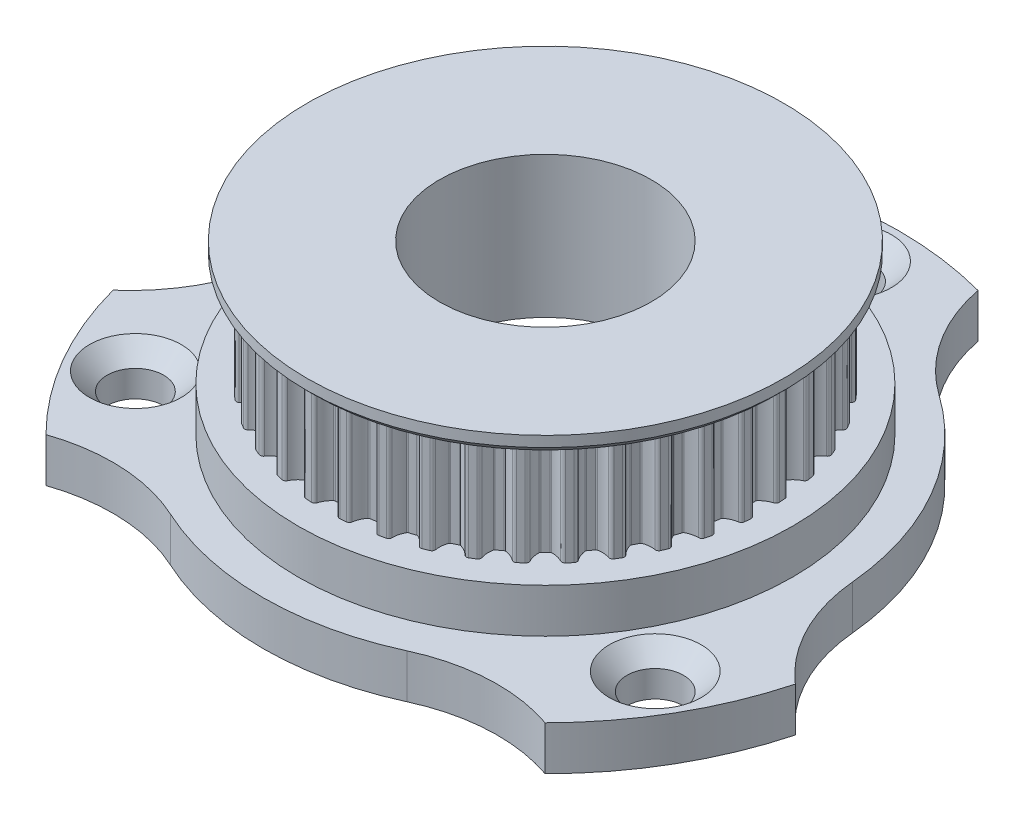
SolidWorks part; units mm, degrees
ref_plane "Front Plane" through (0, 0, 0) normal (0, 0, 1) x (1, 0, 0)
ref_plane "Top Plane" through (0, 0, 0) normal (0, 1, 0) x (1, 0, 0)
ref_plane "Right Plane" through (0, 0, 0) normal (1, 0, 0) x (0, 0, -1)
sketch "Sketch1" plane through (0, 0, 0) normal (0, 1, 0) x (1, 0, 0)
  line L0 (0, 0) -> (0, 17) construction
  circle A1 centre (0, 0) radius 13
  circle A2 centre (0, 17) radius 1.6
  circle A3 centre (14.7224, -8.5) radius 1.6
  circle A4 centre (-14.7224, -8.5) radius 1.6
  arc A7 (-9.2308, 13.0688) -> (-5.1862, 19.3159) centre (-15, 21.2368) ccw
  arc A8 (-9.2308, 13.0688) -> (-15.9333, 1.4597) centre (0, 0) ccw
  arc A9 (-19.3212, -5.1665) -> (-15.9333, 1.4597) centre (-25.8916, 2.372) ccw
  arc A10 (-6.7025, -14.5285) -> (-14.1349, -14.1493) centre (-10.8916, -23.6088) ccw
  arc A11 (-6.7025, -14.5285) -> (6.7025, -14.5285) centre (0, 0) ccw
  arc A12 (14.1349, -14.1493) -> (6.7025, -14.5285) centre (10.8916, -23.6088) ccw
  arc A13 (15.9333, 1.4597) -> (19.3212, -5.1665) centre (25.8916, 2.372) ccw
  arc A14 (15.9333, 1.4597) -> (9.2308, 13.0688) centre (0, 0) ccw
  arc A15 (5.1862, 19.3159) -> (9.2308, 13.0688) centre (15, 21.2368) ccw
  arc A16 (-19.3212, -5.1665) -> (-14.1349, -14.1493) centre (0, 0) ccw
  arc A17 (5.1862, 19.3159) -> (-5.1862, 19.3159) centre (0, 0) ccw
  arc A18 (14.1349, -14.1493) -> (19.3212, -5.1665) centre (0, 0) ccw
  point P13 (0, 0)
  dimension "D1" = 40
  dimension "D2" = 26
  dimension "D3" = 3.2
  dimension "D4" = 17
  dimension "D5" = 3
extrude "Boss-Extrude1" add sketch "Sketch1" along normal blind 4
sketch "Sketch2" plane through (0, 4, 0) normal (0, 1, 0) x (1, 0, 0)
  circle A0 centre (0, 0) radius 14
  dimension "D1" = 28
extrude "Boss-Extrude2" add sketch "Sketch2" along normal blind 1
sketch "Sketch3" plane through (0, 5, 0) normal (0, 1, 0) x (1, 0, 0)
  circle B0 centre (0, 0) radius 1
  arc B1 (0.8079, 12.4518) -> (0.6143, 12.319) centre (0.7956, 12.2622) ccw
  arc B2 (0.2503, 11.7432) -> (0.6143, 12.319) centre (-0.65, 12.7154) ccw
  arc B3 (0.1808, 11.7166) -> (0.2503, 11.7432) centre (0.1823, 11.8166) ccw
  arc B4 (0.1808, 11.7166) -> (-0.1808, 11.7166) centre (0, 0) ccw
  arc B5 (-0.2503, 11.7432) -> (-0.1808, 11.7166) centre (-0.1823, 11.8166) ccw
  arc B6 (-0.6143, 12.319) -> (-0.2503, 11.7432) centre (0.65, 12.7154) ccw
  arc B7 (-0.6143, 12.319) -> (-0.8079, 12.4518) centre (-0.7956, 12.2622) ccw
  arc B8 (-0.8079, 12.4518) -> (-1.1499, 12.4249) centre (0, 0) ccw
  arc B9 (-1.1499, 12.4249) -> (-1.3204, 12.2635) centre (-1.1324, 12.2357) ccw
  arc B10 (-1.5898, 11.6378) -> (-1.3204, 12.2635) centre (-2.6311, 12.4572) ccw
  arc B11 (-1.6543, 11.6006) -> (-1.5898, 11.6378) centre (-1.6684, 11.6996) ccw
  arc B12 (-1.6543, 11.6006) -> (-2.0114, 11.5441) centre (0, 0) ccw
  arc B13 (-2.0842, 11.5595) -> (-2.0114, 11.5441) centre (-2.0286, 11.6426) ccw
  arc B14 (-2.5339, 12.0713) -> (-2.0842, 11.5595) centre (-1.3471, 12.6605) ccw
  arc B15 (-2.5339, 12.0713) -> (-2.7459, 12.1721) centre (-2.7041, 11.9868) ccw
  arc B16 (-2.7459, 12.1721) -> (-3.0794, 12.092) centre (0, 0) ccw
  arc B17 (-3.0794, 12.092) -> (-3.2225, 11.906) centre (-3.0325, 11.9079) ccw
  arc B18 (-3.3908, 11.2458) -> (-3.2225, 11.906) centre (-4.5475, 11.8922) ccw
  arc B19 (-3.4487, 11.199) -> (-3.3908, 11.2458) centre (-3.4781, 11.2946) ccw
  arc B20 (-3.4487, 11.199) -> (-3.7926, 11.0873) centre (0, 0) ccw
  arc B21 (-3.8669, 11.0911) -> (-3.7926, 11.0873) centre (-3.8249, 11.1819) ccw
  arc B22 (-4.3911, 11.5263) -> (-3.8669, 11.0911) centre (-3.3111, 12.2939) ccw
  arc B23 (-4.3911, 11.5263) -> (-4.6162, 11.5927) centre (-4.5459, 11.4162) ccw
  arc B24 (-4.6162, 11.5927) -> (-4.9331, 11.4614) centre (0, 0) ccw
  arc B25 (-4.9331, 11.4614) -> (-5.0454, 11.2553) centre (-4.858, 11.2869) ccw
  arc B26 (-5.1083, 10.5769) -> (-5.0454, 11.2553) centre (-6.3518, 11.0344) ccw
  arc B27 (-5.1581, 10.5216) -> (-5.1083, 10.5769) centre (-5.2022, 10.6114) ccw
  arc B28 (-5.1581, 10.5216) -> (-5.4803, 10.3575) centre (0, 0) ccw
  arc B29 (-5.5543, 10.3497) -> (-5.4803, 10.3575) centre (-5.5271, 10.4459) ccw
  arc B30 (-6.1401, 10.6975) -> (-5.5543, 10.3497) centre (-5.1935, 11.6246) ccw
  arc B31 (-6.1401, 10.6975) -> (-6.3729, 10.7279) centre (-6.2758, 10.5645) ccw
  arc B32 (-6.3729, 10.7279) -> (-6.6654, 10.5486) centre (0, 0) ccw
  arc B33 (-6.6654, 10.5486) -> (-6.744, 10.3274) centre (-6.5639, 10.388) ccw
  arc B34 (-6.7, 9.6476) -> (-6.744, 10.3274) centre (-7.9998, 9.9049) ccw
  arc B35 (-6.7406, 9.5852) -> (-6.7, 9.6476) centre (-6.7981, 9.667) ccw
  arc B36 (-6.7406, 9.5852) -> (-7.0331, 9.3727) centre (0, 0) ccw
  arc B37 (-7.105, 9.3534) -> (-7.0331, 9.3727) centre (-7.0931, 9.4527) ccw
  arc B38 (-7.738, 9.6052) -> (-7.105, 9.3534) centre (-6.9481, 10.669) ccw
  arc B39 (-7.738, 9.6052) -> (-7.9726, 9.5988) centre (-7.8512, 9.4527) ccw
  arc B40 (-7.9726, 9.5988) -> (-8.2335, 9.3761) centre (0, 0) ccw
  arc B41 (-8.2335, 9.3761) -> (-8.2765, 9.1453) centre (-8.1081, 9.2333) ccw
  arc B42 (-8.1267, 8.4807) -> (-8.2765, 9.1453) centre (-9.4508, 8.5315) ccw
  arc B43 (-8.1571, 8.4127) -> (-8.1267, 8.4807) centre (-8.2267, 8.4845) ccw
  arc B44 (-8.1571, 8.4127) -> (-8.4127, 8.1571) centre (0, 0) ccw
  arc B45 (-8.4807, 8.1267) -> (-8.4127, 8.1571) centre (-8.4845, 8.2267) ccw
  arc B46 (-9.1453, 8.2765) -> (-8.4807, 8.1267) centre (-8.5315, 9.4508) ccw
  arc B47 (-9.1453, 8.2765) -> (-9.3761, 8.2335) centre (-9.2333, 8.1081) ccw
  arc B48 (-9.3761, 8.2335) -> (-9.5988, 7.9726) centre (0, 0) ccw
  arc B49 (-9.5988, 7.9726) -> (-9.6052, 7.738) centre (-9.4527, 7.8512) ccw
  arc B50 (-9.3534, 7.105) -> (-9.6052, 7.738) centre (-10.669, 6.9481) ccw
  arc B51 (-9.3727, 7.0331) -> (-9.3534, 7.105) centre (-9.4527, 7.0931) ccw
  arc B52 (-9.3727, 7.0331) -> (-9.5852, 6.7406) centre (0, 0) ccw
  arc B53 (-9.6476, 6.7) -> (-9.5852, 6.7406) centre (-9.667, 6.7981) ccw
  arc B54 (-10.3274, 6.744) -> (-9.6476, 6.7) centre (-9.9049, 7.9998) ccw
  arc B55 (-10.3274, 6.744) -> (-10.5486, 6.6654) centre (-10.388, 6.5639) ccw
  arc B56 (-10.5486, 6.6654) -> (-10.7279, 6.3729) centre (0, 0) ccw
  arc B57 (-10.7279, 6.3729) -> (-10.6975, 6.1401) centre (-10.5645, 6.2758) ccw
  arc B58 (-10.3497, 5.5543) -> (-10.6975, 6.1401) centre (-11.6246, 5.1935) ccw
  arc B59 (-10.3575, 5.4803) -> (-10.3497, 5.5543) centre (-10.4459, 5.5271) ccw
  arc B60 (-10.3575, 5.4803) -> (-10.5216, 5.1581) centre (0, 0) ccw
  arc B61 (-10.5769, 5.1083) -> (-10.5216, 5.1581) centre (-10.6114, 5.2022) ccw
  arc B62 (-11.2553, 5.0454) -> (-10.5769, 5.1083) centre (-11.0344, 6.3518) ccw
  arc B63 (-11.2553, 5.0454) -> (-11.4614, 4.9331) centre (-11.2869, 4.858) ccw
  arc B64 (-11.4614, 4.9331) -> (-11.5927, 4.6162) centre (0, 0) ccw
  arc B65 (-11.5927, 4.6162) -> (-11.5263, 4.3911) centre (-11.4162, 4.5459) ccw
  arc B66 (-11.0911, 3.8669) -> (-11.5263, 4.3911) centre (-12.2939, 3.3111) ccw
  arc B67 (-11.0873, 3.7926) -> (-11.0911, 3.8669) centre (-11.1819, 3.8249) ccw
  arc B68 (-11.0873, 3.7926) -> (-11.199, 3.4487) centre (0, 0) ccw
  arc B69 (-11.2458, 3.3908) -> (-11.199, 3.4487) centre (-11.2946, 3.4781) ccw
  arc B70 (-11.906, 3.2225) -> (-11.2458, 3.3908) centre (-11.8922, 4.5475) ccw
  arc B71 (-11.906, 3.2225) -> (-12.092, 3.0794) centre (-11.9079, 3.0325) ccw
  arc B72 (-12.092, 3.0794) -> (-12.1721, 2.7459) centre (0, 0) ccw
  arc B73 (-12.1721, 2.7459) -> (-12.0713, 2.5339) centre (-11.9868, 2.7041) ccw
  arc B74 (-11.5595, 2.0842) -> (-12.0713, 2.5339) centre (-12.6605, 1.3471) ccw
  arc B75 (-11.5441, 2.0114) -> (-11.5595, 2.0842) centre (-11.6426, 2.0286) ccw
  arc B76 (-11.5441, 2.0114) -> (-11.6006, 1.6543) centre (0, 0) ccw
  arc B77 (-11.6378, 1.5898) -> (-11.6006, 1.6543) centre (-11.6996, 1.6684) ccw
  arc B78 (-12.2635, 1.3204) -> (-11.6378, 1.5898) centre (-12.4572, 2.6311) ccw
  arc B79 (-12.2635, 1.3204) -> (-12.4249, 1.1499) centre (-12.2357, 1.1324) ccw
  arc B80 (-12.4249, 1.1499) -> (-12.4518, 0.8079) centre (0, 0) ccw
  arc B81 (-12.4518, 0.8079) -> (-12.319, 0.6143) centre (-12.2622, 0.7956) ccw
  arc B82 (-11.7432, 0.2503) -> (-12.319, 0.6143) centre (-12.7154, -0.65) ccw
  arc B83 (-11.7166, 0.1808) -> (-11.7432, 0.2503) centre (-11.8166, 0.1823) ccw
  arc B84 (-11.7166, 0.1808) -> (-11.7166, -0.1808) centre (0, 0) ccw
  arc B85 (-11.7432, -0.2503) -> (-11.7166, -0.1808) centre (-11.8166, -0.1823) ccw
  arc B86 (-12.319, -0.6143) -> (-11.7432, -0.2503) centre (-12.7154, 0.65) ccw
  arc B87 (-12.319, -0.6143) -> (-12.4518, -0.8079) centre (-12.2622, -0.7956) ccw
  arc B88 (-12.4518, -0.8079) -> (-12.4249, -1.1499) centre (0, 0) ccw
  arc B89 (-12.4249, -1.1499) -> (-12.2635, -1.3204) centre (-12.2357, -1.1324) ccw
  arc B90 (-11.6378, -1.5898) -> (-12.2635, -1.3204) centre (-12.4572, -2.6311) ccw
  arc B91 (-11.6006, -1.6543) -> (-11.6378, -1.5898) centre (-11.6996, -1.6684) ccw
  arc B92 (-11.6006, -1.6543) -> (-11.5441, -2.0114) centre (0, 0) ccw
  arc B93 (-11.5595, -2.0842) -> (-11.5441, -2.0114) centre (-11.6426, -2.0286) ccw
  arc B94 (-12.0713, -2.5339) -> (-11.5595, -2.0842) centre (-12.6605, -1.3471) ccw
  arc B95 (-12.0713, -2.5339) -> (-12.1721, -2.7459) centre (-11.9868, -2.7041) ccw
  arc B96 (-12.1721, -2.7459) -> (-12.092, -3.0794) centre (0, 0) ccw
  arc B97 (-12.092, -3.0794) -> (-11.906, -3.2225) centre (-11.9079, -3.0325) ccw
  arc B98 (-11.2458, -3.3908) -> (-11.906, -3.2225) centre (-11.8922, -4.5475) ccw
  arc B99 (-11.199, -3.4487) -> (-11.2458, -3.3908) centre (-11.2946, -3.4781) ccw
  arc B100 (-11.199, -3.4487) -> (-11.0873, -3.7926) centre (0, 0) ccw
  arc B101 (-11.0911, -3.8669) -> (-11.0873, -3.7926) centre (-11.1819, -3.8249) ccw
  arc B102 (-11.5263, -4.3911) -> (-11.0911, -3.8669) centre (-12.2939, -3.3111) ccw
  arc B103 (-11.5263, -4.3911) -> (-11.5927, -4.6162) centre (-11.4162, -4.5459) ccw
  arc B104 (-11.5927, -4.6162) -> (-11.4614, -4.9331) centre (0, 0) ccw
  arc B105 (-11.4614, -4.9331) -> (-11.2553, -5.0454) centre (-11.2869, -4.858) ccw
  arc B106 (-10.5769, -5.1083) -> (-11.2553, -5.0454) centre (-11.0344, -6.3518) ccw
  arc B107 (-10.5216, -5.1581) -> (-10.5769, -5.1083) centre (-10.6114, -5.2022) ccw
  arc B108 (-10.5216, -5.1581) -> (-10.3575, -5.4803) centre (0, 0) ccw
  arc B109 (-10.3497, -5.5543) -> (-10.3575, -5.4803) centre (-10.4459, -5.5271) ccw
  arc B110 (-10.6975, -6.1401) -> (-10.3497, -5.5543) centre (-11.6246, -5.1935) ccw
  arc B111 (-10.6975, -6.1401) -> (-10.7279, -6.3729) centre (-10.5645, -6.2758) ccw
  arc B112 (-10.7279, -6.3729) -> (-10.5486, -6.6654) centre (0, 0) ccw
  arc B113 (-10.5486, -6.6654) -> (-10.3274, -6.744) centre (-10.388, -6.5639) ccw
  arc B114 (-9.6476, -6.7) -> (-10.3274, -6.744) centre (-9.9049, -7.9998) ccw
  arc B115 (-9.5852, -6.7406) -> (-9.6476, -6.7) centre (-9.667, -6.7981) ccw
  arc B116 (-9.5852, -6.7406) -> (-9.3727, -7.0331) centre (0, 0) ccw
  arc B117 (-9.3534, -7.105) -> (-9.3727, -7.0331) centre (-9.4527, -7.0931) ccw
  arc B118 (-9.6052, -7.738) -> (-9.3534, -7.105) centre (-10.669, -6.9481) ccw
  arc B119 (-9.6052, -7.738) -> (-9.5988, -7.9726) centre (-9.4527, -7.8512) ccw
  arc B120 (-9.5988, -7.9726) -> (-9.3761, -8.2335) centre (0, 0) ccw
  arc B121 (-9.3761, -8.2335) -> (-9.1453, -8.2765) centre (-9.2333, -8.1081) ccw
  arc B122 (-8.4807, -8.1267) -> (-9.1453, -8.2765) centre (-8.5315, -9.4508) ccw
  arc B123 (-8.4127, -8.1571) -> (-8.4807, -8.1267) centre (-8.4845, -8.2267) ccw
  arc B124 (-8.4127, -8.1571) -> (-8.1571, -8.4127) centre (0, 0) ccw
  arc B125 (-8.1267, -8.4807) -> (-8.1571, -8.4127) centre (-8.2267, -8.4845) ccw
  arc B126 (-8.2765, -9.1453) -> (-8.1267, -8.4807) centre (-9.4508, -8.5315) ccw
  arc B127 (-8.2765, -9.1453) -> (-8.2335, -9.3761) centre (-8.1081, -9.2333) ccw
  arc B128 (-8.2335, -9.3761) -> (-7.9726, -9.5988) centre (0, 0) ccw
  arc B129 (-7.9726, -9.5988) -> (-7.738, -9.6052) centre (-7.8512, -9.4527) ccw
  arc B130 (-7.105, -9.3534) -> (-7.738, -9.6052) centre (-6.9481, -10.669) ccw
  arc B131 (-7.0331, -9.3727) -> (-7.105, -9.3534) centre (-7.0931, -9.4527) ccw
  arc B132 (-7.0331, -9.3727) -> (-6.7406, -9.5852) centre (0, 0) ccw
  arc B133 (-6.7, -9.6476) -> (-6.7406, -9.5852) centre (-6.7981, -9.667) ccw
  arc B134 (-6.744, -10.3274) -> (-6.7, -9.6476) centre (-7.9998, -9.9049) ccw
  arc B135 (-6.744, -10.3274) -> (-6.6654, -10.5486) centre (-6.5639, -10.388) ccw
  arc B136 (-6.6654, -10.5486) -> (-6.3729, -10.7279) centre (0, 0) ccw
  arc B137 (-6.3729, -10.7279) -> (-6.1401, -10.6975) centre (-6.2758, -10.5645) ccw
  arc B138 (-5.5543, -10.3497) -> (-6.1401, -10.6975) centre (-5.1935, -11.6246) ccw
  arc B139 (-5.4803, -10.3575) -> (-5.5543, -10.3497) centre (-5.5271, -10.4459) ccw
  arc B140 (-5.4803, -10.3575) -> (-5.1581, -10.5216) centre (0, 0) ccw
  arc B141 (-5.1083, -10.5769) -> (-5.1581, -10.5216) centre (-5.2022, -10.6114) ccw
  arc B142 (-5.0454, -11.2553) -> (-5.1083, -10.5769) centre (-6.3518, -11.0344) ccw
  arc B143 (-5.0454, -11.2553) -> (-4.9331, -11.4614) centre (-4.858, -11.2869) ccw
  arc B144 (-4.9331, -11.4614) -> (-4.6162, -11.5927) centre (0, 0) ccw
  arc B145 (-4.6162, -11.5927) -> (-4.3911, -11.5263) centre (-4.5459, -11.4162) ccw
  arc B146 (-3.8669, -11.0911) -> (-4.3911, -11.5263) centre (-3.3111, -12.2939) ccw
  arc B147 (-3.7926, -11.0873) -> (-3.8669, -11.0911) centre (-3.8249, -11.1819) ccw
  arc B148 (-3.7926, -11.0873) -> (-3.4487, -11.199) centre (0, 0) ccw
  arc B149 (-3.3908, -11.2458) -> (-3.4487, -11.199) centre (-3.4781, -11.2946) ccw
  arc B150 (-3.2225, -11.906) -> (-3.3908, -11.2458) centre (-4.5475, -11.8922) ccw
  arc B151 (-3.2225, -11.906) -> (-3.0794, -12.092) centre (-3.0325, -11.9079) ccw
  arc B152 (-3.0794, -12.092) -> (-2.7459, -12.1721) centre (0, 0) ccw
  arc B153 (-2.7459, -12.1721) -> (-2.5339, -12.0713) centre (-2.7041, -11.9868) ccw
  arc B154 (-2.0842, -11.5595) -> (-2.5339, -12.0713) centre (-1.3471, -12.6605) ccw
  arc B155 (-2.0114, -11.5441) -> (-2.0842, -11.5595) centre (-2.0286, -11.6426) ccw
  arc B156 (-2.0114, -11.5441) -> (-1.6543, -11.6006) centre (0, 0) ccw
  arc B157 (-1.5898, -11.6378) -> (-1.6543, -11.6006) centre (-1.6684, -11.6996) ccw
  arc B158 (-1.3204, -12.2635) -> (-1.5898, -11.6378) centre (-2.6311, -12.4572) ccw
  arc B159 (-1.3204, -12.2635) -> (-1.1499, -12.4249) centre (-1.1324, -12.2357) ccw
  arc B160 (-1.1499, -12.4249) -> (-0.8079, -12.4518) centre (0, 0) ccw
  arc B161 (-0.8079, -12.4518) -> (-0.6143, -12.319) centre (-0.7956, -12.2622) ccw
  arc B162 (-0.2503, -11.7432) -> (-0.6143, -12.319) centre (0.65, -12.7154) ccw
  arc B163 (-0.1808, -11.7166) -> (-0.2503, -11.7432) centre (-0.1823, -11.8166) ccw
  arc B164 (-0.1808, -11.7166) -> (0.1808, -11.7166) centre (0, 0) ccw
  arc B165 (0.2503, -11.7432) -> (0.1808, -11.7166) centre (0.1823, -11.8166) ccw
  arc B166 (0.6143, -12.319) -> (0.2503, -11.7432) centre (-0.65, -12.7154) ccw
  arc B167 (0.6143, -12.319) -> (0.8079, -12.4518) centre (0.7956, -12.2622) ccw
  arc B168 (0.8079, -12.4518) -> (1.1499, -12.4249) centre (0, 0) ccw
  arc B169 (1.1499, -12.4249) -> (1.3204, -12.2635) centre (1.1324, -12.2357) ccw
  arc B170 (1.5898, -11.6378) -> (1.3204, -12.2635) centre (2.6311, -12.4572) ccw
  arc B171 (1.6543, -11.6006) -> (1.5898, -11.6378) centre (1.6684, -11.6996) ccw
  arc B172 (1.6543, -11.6006) -> (2.0114, -11.5441) centre (0, 0) ccw
  arc B173 (2.0842, -11.5595) -> (2.0114, -11.5441) centre (2.0286, -11.6426) ccw
  arc B174 (2.5339, -12.0713) -> (2.0842, -11.5595) centre (1.3471, -12.6605) ccw
  arc B175 (2.5339, -12.0713) -> (2.7459, -12.1721) centre (2.7041, -11.9868) ccw
  arc B176 (2.7459, -12.1721) -> (3.0794, -12.092) centre (0, 0) ccw
  arc B177 (3.0794, -12.092) -> (3.2225, -11.906) centre (3.0325, -11.9079) ccw
  arc B178 (3.3908, -11.2458) -> (3.2225, -11.906) centre (4.5475, -11.8922) ccw
  arc B179 (3.4487, -11.199) -> (3.3908, -11.2458) centre (3.4781, -11.2946) ccw
  arc B180 (3.4487, -11.199) -> (3.7926, -11.0873) centre (0, 0) ccw
  arc B181 (3.8669, -11.0911) -> (3.7926, -11.0873) centre (3.8249, -11.1819) ccw
  arc B182 (4.3911, -11.5263) -> (3.8669, -11.0911) centre (3.3111, -12.2939) ccw
  arc B183 (4.3911, -11.5263) -> (4.6162, -11.5927) centre (4.5459, -11.4162) ccw
  arc B184 (4.6162, -11.5927) -> (4.9331, -11.4614) centre (0, 0) ccw
  arc B185 (4.9331, -11.4614) -> (5.0454, -11.2553) centre (4.858, -11.2869) ccw
  arc B186 (5.1083, -10.5769) -> (5.0454, -11.2553) centre (6.3518, -11.0344) ccw
  arc B187 (5.1581, -10.5216) -> (5.1083, -10.5769) centre (5.2022, -10.6114) ccw
  arc B188 (5.1581, -10.5216) -> (5.4803, -10.3575) centre (0, 0) ccw
  arc B189 (5.5543, -10.3497) -> (5.4803, -10.3575) centre (5.5271, -10.4459) ccw
  arc B190 (6.1401, -10.6975) -> (5.5543, -10.3497) centre (5.1935, -11.6246) ccw
  arc B191 (6.1401, -10.6975) -> (6.3729, -10.7279) centre (6.2758, -10.5645) ccw
  arc B192 (6.3729, -10.7279) -> (6.6654, -10.5486) centre (0, 0) ccw
  arc B193 (6.6654, -10.5486) -> (6.744, -10.3274) centre (6.5639, -10.388) ccw
  arc B194 (6.7, -9.6476) -> (6.744, -10.3274) centre (7.9998, -9.9049) ccw
  arc B195 (6.7406, -9.5852) -> (6.7, -9.6476) centre (6.7981, -9.667) ccw
  arc B196 (6.7406, -9.5852) -> (7.0331, -9.3727) centre (0, 0) ccw
  arc B197 (7.105, -9.3534) -> (7.0331, -9.3727) centre (7.0931, -9.4527) ccw
  arc B198 (7.738, -9.6052) -> (7.105, -9.3534) centre (6.9481, -10.669) ccw
  arc B199 (7.738, -9.6052) -> (7.9726, -9.5988) centre (7.8512, -9.4527) ccw
  arc B200 (7.9726, -9.5988) -> (8.2335, -9.3761) centre (0, 0) ccw
  arc B201 (8.2335, -9.3761) -> (8.2765, -9.1453) centre (8.1081, -9.2333) ccw
  arc B202 (8.1267, -8.4807) -> (8.2765, -9.1453) centre (9.4508, -8.5315) ccw
  arc B203 (8.1571, -8.4127) -> (8.1267, -8.4807) centre (8.2267, -8.4845) ccw
  arc B204 (8.1571, -8.4127) -> (8.4127, -8.1571) centre (0, 0) ccw
  arc B205 (8.4807, -8.1267) -> (8.4127, -8.1571) centre (8.4845, -8.2267) ccw
  arc B206 (9.1453, -8.2765) -> (8.4807, -8.1267) centre (8.5315, -9.4508) ccw
  arc B207 (9.1453, -8.2765) -> (9.3761, -8.2335) centre (9.2333, -8.1081) ccw
  arc B208 (9.3761, -8.2335) -> (9.5988, -7.9726) centre (0, 0) ccw
  arc B209 (9.5988, -7.9726) -> (9.6052, -7.738) centre (9.4527, -7.8512) ccw
  arc B210 (9.3534, -7.105) -> (9.6052, -7.738) centre (10.669, -6.9481) ccw
  arc B211 (9.3727, -7.0331) -> (9.3534, -7.105) centre (9.4527, -7.0931) ccw
  arc B212 (9.3727, -7.0331) -> (9.5852, -6.7406) centre (0, 0) ccw
  arc B213 (9.6476, -6.7) -> (9.5852, -6.7406) centre (9.667, -6.7981) ccw
  arc B214 (10.3274, -6.744) -> (9.6476, -6.7) centre (9.9049, -7.9998) ccw
  arc B215 (10.3274, -6.744) -> (10.5486, -6.6654) centre (10.388, -6.5639) ccw
  arc B216 (10.5486, -6.6654) -> (10.7279, -6.3729) centre (0, 0) ccw
  arc B217 (10.7279, -6.3729) -> (10.6975, -6.1401) centre (10.5645, -6.2758) ccw
  arc B218 (10.3497, -5.5543) -> (10.6975, -6.1401) centre (11.6246, -5.1935) ccw
  arc B219 (10.3575, -5.4803) -> (10.3497, -5.5543) centre (10.4459, -5.5271) ccw
  arc B220 (10.3575, -5.4803) -> (10.5216, -5.1581) centre (0, 0) ccw
  arc B221 (10.5769, -5.1083) -> (10.5216, -5.1581) centre (10.6114, -5.2022) ccw
  arc B222 (11.2553, -5.0454) -> (10.5769, -5.1083) centre (11.0344, -6.3518) ccw
  arc B223 (11.2553, -5.0454) -> (11.4614, -4.9331) centre (11.2869, -4.858) ccw
  arc B224 (11.4614, -4.9331) -> (11.5927, -4.6162) centre (0, 0) ccw
  arc B225 (11.5927, -4.6162) -> (11.5263, -4.3911) centre (11.4162, -4.5459) ccw
  arc B226 (11.0911, -3.8669) -> (11.5263, -4.3911) centre (12.2939, -3.3111) ccw
  arc B227 (11.0873, -3.7926) -> (11.0911, -3.8669) centre (11.1819, -3.8249) ccw
  arc B228 (11.0873, -3.7926) -> (11.199, -3.4487) centre (0, 0) ccw
  arc B229 (11.2458, -3.3908) -> (11.199, -3.4487) centre (11.2946, -3.4781) ccw
  arc B230 (11.906, -3.2225) -> (11.2458, -3.3908) centre (11.8922, -4.5475) ccw
  arc B231 (11.906, -3.2225) -> (12.092, -3.0794) centre (11.9079, -3.0325) ccw
  arc B232 (12.092, -3.0794) -> (12.1721, -2.7459) centre (0, 0) ccw
  arc B233 (12.1721, -2.7459) -> (12.0713, -2.5339) centre (11.9868, -2.7041) ccw
  arc B234 (11.5595, -2.0842) -> (12.0713, -2.5339) centre (12.6605, -1.3471) ccw
  arc B235 (11.5441, -2.0114) -> (11.5595, -2.0842) centre (11.6426, -2.0286) ccw
  arc B236 (11.5441, -2.0114) -> (11.6006, -1.6543) centre (0, 0) ccw
  arc B237 (11.6378, -1.5898) -> (11.6006, -1.6543) centre (11.6996, -1.6684) ccw
  arc B238 (12.2635, -1.3204) -> (11.6378, -1.5898) centre (12.4572, -2.6311) ccw
  arc B239 (12.2635, -1.3204) -> (12.4249, -1.1499) centre (12.2357, -1.1324) ccw
  arc B240 (12.4249, -1.1499) -> (12.4518, -0.8079) centre (0, 0) ccw
  arc B241 (12.4518, -0.8079) -> (12.319, -0.6143) centre (12.2622, -0.7956) ccw
  arc B242 (11.7432, -0.2503) -> (12.319, -0.6143) centre (12.7154, 0.65) ccw
  arc B243 (11.7166, -0.1808) -> (11.7432, -0.2503) centre (11.8166, -0.1823) ccw
  arc B244 (11.7166, -0.1808) -> (11.7166, 0.1808) centre (0, 0) ccw
  arc B245 (11.7432, 0.2503) -> (11.7166, 0.1808) centre (11.8166, 0.1823) ccw
  arc B246 (12.319, 0.6143) -> (11.7432, 0.2503) centre (12.7154, -0.65) ccw
  arc B247 (12.319, 0.6143) -> (12.4518, 0.8079) centre (12.2622, 0.7956) ccw
  arc B248 (12.4518, 0.8079) -> (12.4249, 1.1499) centre (0, 0) ccw
  arc B249 (12.4249, 1.1499) -> (12.2635, 1.3204) centre (12.2357, 1.1324) ccw
  arc B250 (11.6378, 1.5898) -> (12.2635, 1.3204) centre (12.4572, 2.6311) ccw
  arc B251 (11.6006, 1.6543) -> (11.6378, 1.5898) centre (11.6996, 1.6684) ccw
  arc B252 (11.6006, 1.6543) -> (11.5441, 2.0114) centre (0, 0) ccw
  arc B253 (11.5595, 2.0842) -> (11.5441, 2.0114) centre (11.6426, 2.0286) ccw
  arc B254 (12.0713, 2.5339) -> (11.5595, 2.0842) centre (12.6605, 1.3471) ccw
  arc B255 (12.0713, 2.5339) -> (12.1721, 2.7459) centre (11.9868, 2.7041) ccw
  arc B256 (12.1721, 2.7459) -> (12.092, 3.0794) centre (0, 0) ccw
  arc B257 (12.092, 3.0794) -> (11.906, 3.2225) centre (11.9079, 3.0325) ccw
  arc B258 (11.2458, 3.3908) -> (11.906, 3.2225) centre (11.8922, 4.5475) ccw
  arc B259 (11.199, 3.4487) -> (11.2458, 3.3908) centre (11.2946, 3.4781) ccw
  arc B260 (11.199, 3.4487) -> (11.0873, 3.7926) centre (0, 0) ccw
  arc B261 (11.0911, 3.8669) -> (11.0873, 3.7926) centre (11.1819, 3.8249) ccw
  arc B262 (11.5263, 4.3911) -> (11.0911, 3.8669) centre (12.2939, 3.3111) ccw
  arc B263 (11.5263, 4.3911) -> (11.5927, 4.6162) centre (11.4162, 4.5459) ccw
  arc B264 (11.5927, 4.6162) -> (11.4614, 4.9331) centre (0, 0) ccw
  arc B265 (11.4614, 4.9331) -> (11.2553, 5.0454) centre (11.2869, 4.858) ccw
  arc B266 (10.5769, 5.1083) -> (11.2553, 5.0454) centre (11.0344, 6.3518) ccw
  arc B267 (10.5216, 5.1581) -> (10.5769, 5.1083) centre (10.6114, 5.2022) ccw
  arc B268 (10.5216, 5.1581) -> (10.3575, 5.4803) centre (0, 0) ccw
  arc B269 (10.3497, 5.5543) -> (10.3575, 5.4803) centre (10.4459, 5.5271) ccw
  arc B270 (10.6975, 6.1401) -> (10.3497, 5.5543) centre (11.6246, 5.1935) ccw
  arc B271 (10.6975, 6.1401) -> (10.7279, 6.3729) centre (10.5645, 6.2758) ccw
  arc B272 (10.7279, 6.3729) -> (10.5486, 6.6654) centre (0, 0) ccw
  arc B273 (10.5486, 6.6654) -> (10.3274, 6.744) centre (10.388, 6.5639) ccw
  arc B274 (9.6476, 6.7) -> (10.3274, 6.744) centre (9.9049, 7.9998) ccw
  arc B275 (9.5852, 6.7406) -> (9.6476, 6.7) centre (9.667, 6.7981) ccw
  arc B276 (9.5852, 6.7406) -> (9.3727, 7.0331) centre (0, 0) ccw
  arc B277 (9.3534, 7.105) -> (9.3727, 7.0331) centre (9.4527, 7.0931) ccw
  arc B278 (9.6052, 7.738) -> (9.3534, 7.105) centre (10.669, 6.9481) ccw
  arc B279 (9.6052, 7.738) -> (9.5988, 7.9726) centre (9.4527, 7.8512) ccw
  arc B280 (9.5988, 7.9726) -> (9.3761, 8.2335) centre (0, 0) ccw
  arc B281 (9.3761, 8.2335) -> (9.1453, 8.2765) centre (9.2333, 8.1081) ccw
  arc B282 (8.4807, 8.1267) -> (9.1453, 8.2765) centre (8.5315, 9.4508) ccw
  arc B283 (8.4127, 8.1571) -> (8.4807, 8.1267) centre (8.4845, 8.2267) ccw
  arc B284 (8.4127, 8.1571) -> (8.1571, 8.4127) centre (0, 0) ccw
  arc B285 (8.1267, 8.4807) -> (8.1571, 8.4127) centre (8.2267, 8.4845) ccw
  arc B286 (8.2765, 9.1453) -> (8.1267, 8.4807) centre (9.4508, 8.5315) ccw
  arc B287 (8.2765, 9.1453) -> (8.2335, 9.3761) centre (8.1081, 9.2333) ccw
  arc B288 (8.2335, 9.3761) -> (7.9726, 9.5988) centre (0, 0) ccw
  arc B289 (7.9726, 9.5988) -> (7.738, 9.6052) centre (7.8512, 9.4527) ccw
  arc B290 (7.105, 9.3534) -> (7.738, 9.6052) centre (6.9481, 10.669) ccw
  arc B291 (7.0331, 9.3727) -> (7.105, 9.3534) centre (7.0931, 9.4527) ccw
  arc B292 (7.0331, 9.3727) -> (6.7406, 9.5852) centre (0, 0) ccw
  arc B293 (6.7, 9.6476) -> (6.7406, 9.5852) centre (6.7981, 9.667) ccw
  arc B294 (6.744, 10.3274) -> (6.7, 9.6476) centre (7.9998, 9.9049) ccw
  arc B295 (6.744, 10.3274) -> (6.6654, 10.5486) centre (6.5639, 10.388) ccw
  arc B296 (6.6654, 10.5486) -> (6.3729, 10.7279) centre (0, 0) ccw
  arc B297 (6.3729, 10.7279) -> (6.1401, 10.6975) centre (6.2758, 10.5645) ccw
  arc B298 (5.5543, 10.3497) -> (6.1401, 10.6975) centre (5.1935, 11.6246) ccw
  arc B299 (5.4803, 10.3575) -> (5.5543, 10.3497) centre (5.5271, 10.4459) ccw
  arc B300 (5.4803, 10.3575) -> (5.1581, 10.5216) centre (0, 0) ccw
  arc B301 (5.1083, 10.5769) -> (5.1581, 10.5216) centre (5.2022, 10.6114) ccw
  arc B302 (5.0454, 11.2553) -> (5.1083, 10.5769) centre (6.3518, 11.0344) ccw
  arc B303 (5.0454, 11.2553) -> (4.9331, 11.4614) centre (4.858, 11.2869) ccw
  arc B304 (4.9331, 11.4614) -> (4.6162, 11.5927) centre (0, 0) ccw
  arc B305 (4.6162, 11.5927) -> (4.3911, 11.5263) centre (4.5459, 11.4162) ccw
  arc B306 (3.8669, 11.0911) -> (4.3911, 11.5263) centre (3.3111, 12.2939) ccw
  arc B307 (3.7926, 11.0873) -> (3.8669, 11.0911) centre (3.8249, 11.1819) ccw
  arc B308 (3.7926, 11.0873) -> (3.4487, 11.199) centre (0, 0) ccw
  arc B309 (3.3908, 11.2458) -> (3.4487, 11.199) centre (3.4781, 11.2946) ccw
  arc B310 (3.2225, 11.906) -> (3.3908, 11.2458) centre (4.5475, 11.8922) ccw
  arc B311 (3.2225, 11.906) -> (3.0794, 12.092) centre (3.0325, 11.9079) ccw
  arc B312 (3.0794, 12.092) -> (2.7459, 12.1721) centre (0, 0) ccw
  arc B313 (2.7459, 12.1721) -> (2.5339, 12.0713) centre (2.7041, 11.9868) ccw
  arc B314 (2.0842, 11.5595) -> (2.5339, 12.0713) centre (1.3471, 12.6605) ccw
  arc B315 (2.0114, 11.5441) -> (2.0842, 11.5595) centre (2.0286, 11.6426) ccw
  arc B316 (2.0114, 11.5441) -> (1.6543, 11.6006) centre (0, 0) ccw
  arc B317 (1.5898, 11.6378) -> (1.6543, 11.6006) centre (1.6684, 11.6996) ccw
  arc B318 (1.3204, 12.2635) -> (1.5898, 11.6378) centre (2.6311, 12.4572) ccw
  arc B319 (1.3204, 12.2635) -> (1.1499, 12.4249) centre (1.1324, 12.2357) ccw
  arc B320 (1.1499, 12.4249) -> (0.8079, 12.4518) centre (0, 0) ccw
sketch_block_instance "Block2-1"
sketch_block "Block2"
extrude "Boss-Extrude3" add sketch "Sketch3" along normal blind 6
sketch "Sketch4" plane through (0, 11, 0) normal (0, 1, 0) x (1, 0, 0)
  circle A0 centre (0, 0) radius 13.5
  dimension "D1" = 27
extrude "Boss-Extrude4" add sketch "Sketch4" along normal blind 1
sketch "Sketch5" plane through (0, 12, 0) normal (0, 1, 0) x (1, 0, 0)
  circle A0 centre (0, 0) radius 6
  dimension "D1" = 12
extrude "Cut-Extrude1" cut sketch "Sketch5" against normal through all
chamfer "Chamfer1" distance 0.4 angle 45 1 edges at (0, 11, 13.5)
sketch "Sketch6" plane through (0, 4, 0) normal (0, 1, 0) x (1, 0, 0)
  circle A0 centre (0, 0) radius 14
  arc A12 (-9.2308, 13.0688) -> (-15.9333, 1.4597) centre (0, 0) ccw
  arc A13 (-19.3212, -5.1665) -> (-15.9333, 1.4597) centre (-25.8916, 2.372) ccw
  arc A14 (-19.3212, -5.1665) -> (-14.1349, -14.1493) centre (0, 0) ccw
  arc A15 (-6.7025, -14.5285) -> (-14.1349, -14.1493) centre (-10.8916, -23.6088) ccw
  arc A16 (-6.7025, -14.5285) -> (6.7025, -14.5285) centre (0, 0) ccw
  arc A17 (14.1349, -14.1493) -> (6.7025, -14.5285) centre (10.8916, -23.6088) ccw
  arc A18 (14.1349, -14.1493) -> (19.3212, -5.1665) centre (0, 0) ccw
  arc A19 (15.9333, 1.4597) -> (19.3212, -5.1665) centre (25.8916, 2.372) ccw
  arc A20 (15.9333, 1.4597) -> (9.2308, 13.0688) centre (0, 0) ccw
  arc A21 (5.1862, 19.3159) -> (9.2308, 13.0688) centre (15, 21.2368) ccw
  arc A22 (5.1862, 19.3159) -> (-5.1862, 19.3159) centre (0, 0) ccw
  arc A23 (-9.2308, 13.0688) -> (-5.1862, 19.3159) centre (-15, 21.2368) ccw
  arc A24 (-9.2308, 13.0688) -> (-15.9333, 1.4597) centre (0, 0) ccw
  arc A25 (-19.3212, -5.1665) -> (-15.9333, 1.4597) centre (-25.8916, 2.372) ccw
  arc A26 (-19.3212, -5.1665) -> (-14.1349, -14.1493) centre (0, 0) ccw
  arc A27 (-6.7025, -14.5285) -> (-14.1349, -14.1493) centre (-10.8916, -23.6088) ccw
  arc A28 (-6.7025, -14.5285) -> (6.7025, -14.5285) centre (0, 0) ccw
  arc A29 (14.1349, -14.1493) -> (6.7025, -14.5285) centre (10.8916, -23.6088) ccw
  arc A30 (14.1349, -14.1493) -> (19.3212, -5.1665) centre (0, 0) ccw
  arc A31 (15.9333, 1.4597) -> (19.3212, -5.1665) centre (25.8916, 2.372) ccw
  arc A32 (15.9333, 1.4597) -> (9.2308, 13.0688) centre (0, 0) ccw
  arc A33 (5.1862, 19.3159) -> (9.2308, 13.0688) centre (15, 21.2368) ccw
  arc A34 (5.1862, 19.3159) -> (-5.1862, 19.3159) centre (0, 0) ccw
  arc A35 (-9.2308, 13.0688) -> (-5.1862, 19.3159) centre (-15, 21.2368) ccw
  dimension "D1" = 0
extrude "Cut-Extrude2" cut sketch "Sketch6" against normal blind 1.5
chamfer "Chamfer2" distance 1 angle 45 3 edges at (0, 2.5, -15.4) (-14.7224, 2.5, 10.1) (14.7224, 2.5, 10.1)
